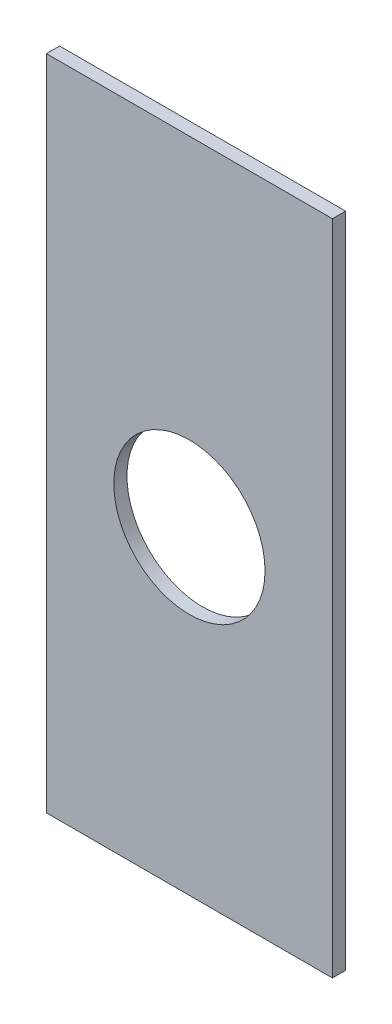
SolidWorks part; units mm, degrees
ref_plane "前视基准面" through (0, 0, 0) normal (0, 0, 1) x (1, 0, 0)
ref_plane "上视基准面" through (0, 0, 0) normal (0, 1, 0) x (1, 0, 0)
ref_plane "右视基准面" through (0, 0, 0) normal (1, 0, 0) x (0, 0, -1)
sketch "草图1" plane through (0, 0, 0) normal (0, 0, 1) x (1, 0, 0)
  line L0 (0, 20) -> (37.5, 20) construction
  line L1 (-37.5, 50) -> (37.5, 50)
  line L2 (-37.5, 50) -> (-37.5, -150) construction
  line L3 (-37.5, -150) -> (37.5, -150)
  line L4 (37.5, 50) -> (37.5, -150) construction
  line L5 (0, 20) -> (-37.5, 20) construction
  line L6 (37.5, -50) -> (43.5, -50) construction
  line L7 (43.5, -50) -> (43.5, -150)
  line L8 (43.5, -150) -> (37.5, -150)
  line L9 (-37.5, -50) -> (-43.5, -50) construction
  line L10 (-43.5, -50) -> (-43.5, -150)
  line L11 (-43.5, -150) -> (-37.5, -150)
  line L12 (-37.5, 50) -> (-37.5, -50) construction
  line L13 (37.5, -50) -> (37.5, 50) construction
  line L14 (-43.5, -50) -> (-43.5, 50)
  line L15 (-43.5, 50) -> (-37.5, 50)
  line L16 (43.5, -50) -> (43.5, 50)
  line L17 (43.5, 50) -> (37.5, 50)
  circle A0 centre (0, 0) radius 4.5 construction
  circle A2 centre (20, 0) radius 2 construction
  circle A3 centre (0, 20) radius 2 construction
  circle A4 centre (-20, 0) radius 2 construction
  circle A5 centre (-20, 40) radius 2 construction
  circle A6 centre (20, 40) radius 2 construction
  circle A7 centre (-20, -40) radius 2 construction
  circle A8 centre (20, -40) radius 2 construction
  circle A9 centre (0, -53) radius 23
  dimension "D1" = 9
  dimension "D4" = 4
  dimension "D9" = 40
  dimension "D2" = 20
  dimension "D3" = 20
  dimension "D6" = 37.5
  dimension "D7" = 200
  dimension "D8" = 10
  dimension "D10" = 40
  dimension "D11" = 6
  dimension "D12" = 53
  dimension "D5" = 4
extrude "凸台-拉伸1" add sketch "草图1" along normal blind 4 contours L3 L4 L1 L2
sketch "草图2" plane through (0, 0, 4) normal (0, 0, 1) x (1, 0, 0)
  line L2 (37.5, -144) -> (37.5, -150) construction
  line L3 (-43.5, -150) -> (43.5, -150) construction
  line L4 (37.5, -64) -> (37.5, -144) construction
  line L5 (35.3, -124.8) -> (39.7, -124.8)
  line L6 (35.3, -124.8) -> (35.3, -133.2)
  line L7 (35.3, -133.2) -> (39.7, -133.2)
  line L8 (39.7, -124.8) -> (39.7, -133.2)
  line L9 (35.3, -124.8) -> (39.7, -133.2) construction
  line L10 (35.3, -133.2) -> (39.7, -124.8) construction
  line L11 (37.5, -104) -> (29.7481, -104) construction
  line L12 (39.7, -83.2) -> (39.7, -74.8)
  line L13 (35.3, -74.8) -> (39.7, -74.8)
  line L14 (35.3, -83.2) -> (35.3, -74.8)
  line L15 (35.3, -83.2) -> (39.7, -83.2)
  line L16 (0, 0) -> (0, -38.3122) construction
  line L17 (-37.5, -104) -> (-29.7481, -104) construction
  line L18 (-35.3, -133.2) -> (-39.7, -124.8) construction
  line L19 (-35.3, -124.8) -> (-39.7, -133.2) construction
  line L20 (-37.5, -64) -> (-37.5, -144) construction
  line L21 (-37.5, -144) -> (-37.5, -150) construction
  line L22 (-43.5, -144) -> (-37.5, -144) construction
  line L23 (-35.3, -83.2) -> (-39.7, -83.2)
  line L24 (-35.3, -83.2) -> (-35.3, -74.8)
  line L25 (-35.3, -74.8) -> (-39.7, -74.8)
  line L26 (-39.7, -83.2) -> (-39.7, -74.8)
  line L27 (-39.7, -124.8) -> (-39.7, -133.2)
  line L28 (-35.3, -133.2) -> (-39.7, -133.2)
  line L29 (-35.3, -124.8) -> (-35.3, -133.2)
  line L30 (-35.3, -124.8) -> (-39.7, -124.8)
  circle A0 centre (37.5, -144) radius 1.5
  circle A1 centre (37.5, -64) radius 1.5
  circle A2 centre (-37.5, -64) radius 1.5
  circle A3 centre (-37.5, -144) radius 1.5
  point P8 (37.5, -129)
  point P40 (-37.5, -129)
  dimension "D2" = 15
  dimension "D5" = 80
  dimension "D6" = 75
  dimension "D1" = 37.5
  dimension "D3" = 4.4
  dimension "D4" = 8.4
